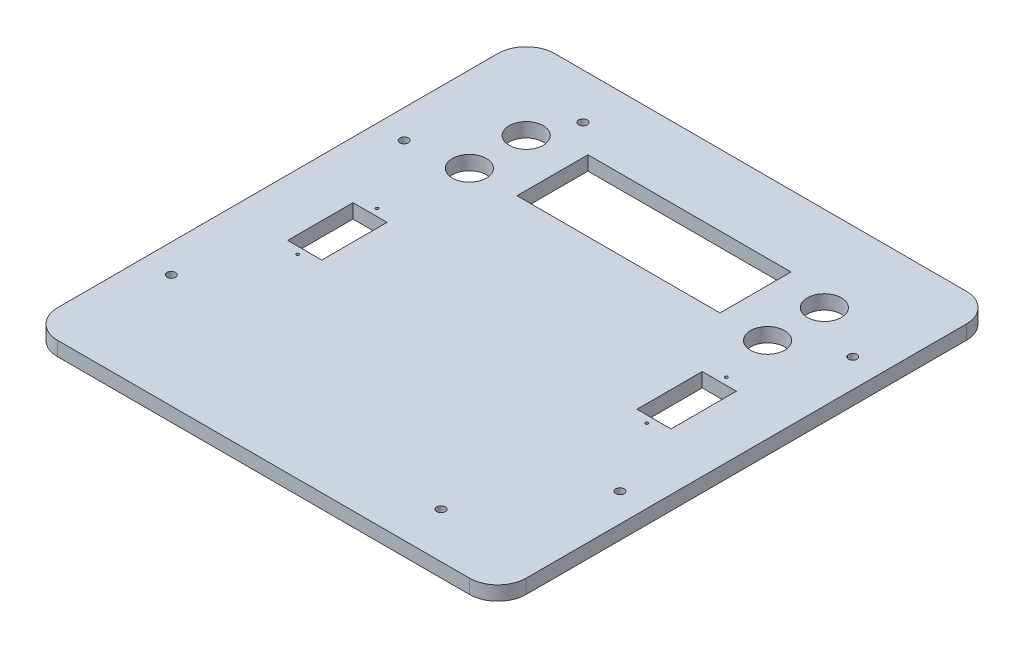
SolidWorks part; units mm, degrees
material "Acrílico (médio-alto impacto)"
ref_plane "Plano frontal" through (0, 0, 0) normal (0, 0, 1) x (1, 0, 0)
ref_plane "Plano superior" through (0, 0, 0) normal (0, 1, 0) x (1, 0, 0)
ref_plane "Plano direito" through (0, 0, 0) normal (1, 0, 0) x (0, 0, -1)
sketch "Esboço1" plane through (0, 0, 0) normal (0, 1, 0) x (1, 0, 0)
  line L1 (-25.4636, 142.2644) -> (119.5364, 142.2644)
  line L2 (-35.4636, 132.2644) -> (-35.4636, -22.7356)
  line L3 (-25.4636, -32.7356) -> (119.5364, -32.7356)
  line L4 (129.5364, 132.2644) -> (129.5364, -22.7356)
  arc A0 (119.5364, 142.2644) -> (129.5364, 132.2644) centre (119.5364, 132.2644) cw
  arc A1 (119.5364, -32.7356) -> (129.5364, -22.7356) centre (119.5364, -22.7356) ccw
  arc A2 (-35.4636, -22.7356) -> (-25.4636, -32.7356) centre (-25.4636, -22.7356) ccw
  arc A3 (-25.4636, 142.2644) -> (-35.4636, 132.2644) centre (-25.4636, 132.2644) ccw
  arc A4 (119.5364, 142.2644) -> (129.5364, 132.2644) centre (119.5364, 132.2644) cw
  dimension "D1" = 10
  dimension "D2" = 10
extrude "Ressalto-extrusão1" add sketch "Esboço1" along normal blind 5 contours L1 A3 L2 A2 L3 A1 L4 A0
sketch "Esboço2" plane through (0, 5, 0) normal (0, 1, 0) x (1, 0, 0)
  line L0 (-35.4636, 132.2644) -> (-35.4636, -22.7356) construction
  line L1 (-25.4636, -32.7356) -> (119.5364, -32.7356) construction
  line L2 (129.5364, 132.2644) -> (129.5364, -22.7356) construction
  line L3 (-25.4636, 142.2644) -> (119.5364, 142.2644) construction
  circle A0 centre (-25.4636, 7.2644) radius 1.5
  circle A1 centre (0.5364, 126.2644) radius 1.5
  circle A2 centre (119.5364, 102.2644) radius 1.5
  circle A3 centre (93.5364, -16.7356) radius 1.5
  dimension "D1" = 10
  dimension "D2" = 40
  dimension "D3" = 10
  dimension "D4" = 40
  dimension "D5" = 16
  dimension "D6" = 36
  dimension "D7" = 36
  dimension "D8" = 16
  dimension "D9" = 3
  dimension "D10" = 3
  dimension "D11" = 3
  dimension "D12" = 3
extrude "Corte-extrusão1" cut sketch "Esboço2" against normal blind 5
sketch "Esboço4" plane through (0, 5, 0) normal (0, 1, 0) x (1, 0, 0)
  line L0 (-35.4636, 132.2644) -> (-35.4636, -22.7356) construction
  line L1 (-25.4636, -32.7356) -> (119.5364, -32.7356) construction
  line L2 (-25.4636, 142.2644) -> (119.5364, 142.2644) construction
  line L3 (129.5364, 132.2644) -> (129.5364, -22.7356) construction
  line L5 (-15.4636, 38.2644) -> (-3.4636, 38.2644)
  line L6 (-15.4636, 38.2644) -> (-15.4636, 61.2644)
  line L7 (-15.4636, 61.2644) -> (-3.4636, 61.2644)
  line L8 (-3.4636, 38.2644) -> (-3.4636, 61.2644)
  line L9 (109.5364, 48.2644) -> (97.5364, 48.2644)
  line L10 (109.5364, 48.2644) -> (109.5364, 71.2644)
  line L11 (109.5364, 71.2644) -> (97.5364, 71.2644)
  line L12 (97.5364, 48.2644) -> (97.5364, 71.2644)
  circle A0 centre (-9.4636, 35.7644) radius 0.5
  circle A1 centre (-9.4636, 63.7644) radius 0.5
  circle A2 centre (103.5364, 45.7644) radius 0.5
  circle A3 centre (103.5364, 73.7644) radius 0.5
  point P24 (129.5364, 54.7644)
  dimension "D1" = 26
  dimension "D2" = 26
  dimension "D3" = 1
  dimension "D4" = 1
  dimension "D5" = 71
  dimension "D6" = 78.5
  dimension "D7" = 78.5
  dimension "D8" = 68.5
  dimension "D9" = 1
  dimension "D10" = 1
  dimension "D11" = 26
  dimension "D12" = 26
  dimension "D13" = 28
  dimension "D14" = 2.5
  dimension "D15" = 2.5
  dimension "D16" = 12
  dimension "D17" = 20
  dimension "D18" = 20
  dimension "D19" = 12
  dimension "D20" = 2.5
  dimension "D21" = 2.5
  dimension "D22" = 23
  dimension "D23" = 23
extrude "Corte-extrusão3" cut sketch "Esboço4" against normal through all
sketch "Esboço5" plane through (0, 5, 0) normal (0, 1, 0) x (1, 0, 0)
  line L0 (-25.4636, 142.2644) -> (119.5364, 142.2644) construction
  line L1 (11.2864, 92.2644) -> (82.7864, 92.2644)
  line L2 (11.2864, 92.2644) -> (11.2864, 117.2644)
  line L3 (11.2864, 117.2644) -> (82.7864, 117.2644)
  line L4 (82.7864, 92.2644) -> (82.7864, 117.2644)
  line L7 (-35.4636, 132.2644) -> (-35.4636, -22.7356) construction
  line L11 (129.5364, 132.2644) -> (129.5364, -22.7356) construction
  line L12 (-25.4636, -32.7356) -> (119.5364, -32.7356) construction
  circle A0 centre (-25.4636, 89.2644) radius 1.5
  circle A1 centre (119.5364, 20.2644) radius 1.5
  dimension "D5" = 3
  dimension "D6" = 53
  dimension "D7" = 10
  dimension "D8" = 3
  dimension "D9" = 10
  dimension "D10" = 53
  dimension "D1" = 25
  dimension "D2" = 25
  dimension "D3" = 71.5
  dimension "D4" = 46.75
extrude "Corte-extrusão4" cut sketch "Esboço5" against normal through all
sketch "Esboço6" plane through (0, 5, 0) normal (0, 1, 0) x (1, 0, 0)
  line L0 (-25.4636, 142.2644) -> (119.5364, 142.2644) construction
  line L1 (129.5364, 132.2644) -> (129.5364, -22.7356) construction
  line L2 (-35.4636, 132.2644) -> (-35.4636, -22.7356) construction
  circle A0 centre (-5.4636, 112.2644) radius 6
  circle A1 centre (-5.4636, 92.2644) radius 6
  circle A2 centre (99.5364, 112.2644) radius 6
  circle A3 centre (99.5364, 92.2644) radius 6
  dimension "D1" = 30
  dimension "D2" = 30
  dimension "D3" = 30
  dimension "D4" = 12
  dimension "D5" = 20
  dimension "D6" = 30
  dimension "D7" = 12
  dimension "D8" = 20
  dimension "D9" = 12
  dimension "D10" = 30
extrude "Corte-extrusão5" cut sketch "Esboço6" against normal through all
